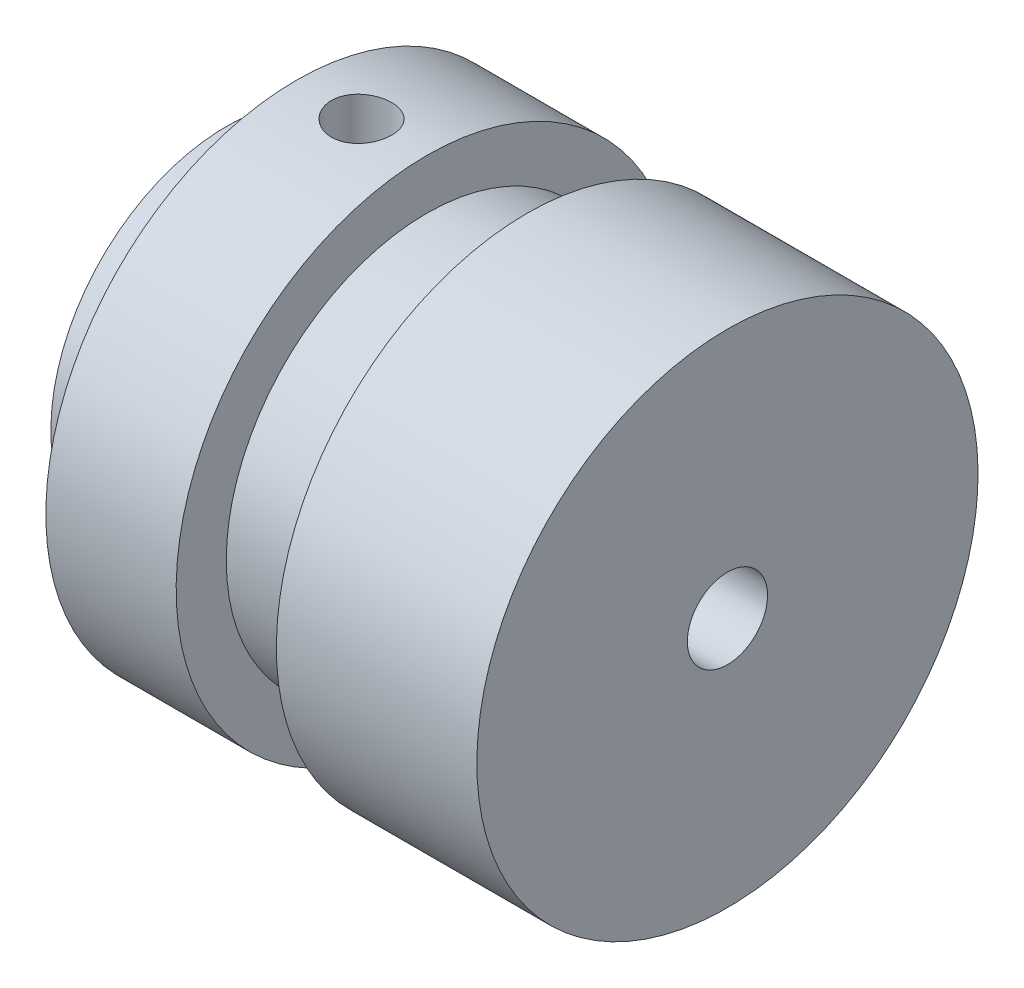
SolidWorks part; units mm, degrees
ref_plane "Front Plane" through (0, 0, 0) normal (0, 0, 1) x (1, 0, 0)
ref_plane "Top Plane" through (0, 0, 0) normal (0, 1, 0) x (1, 0, 0)
ref_plane "Right Plane" through (0, 0, 0) normal (1, 0, 0) x (0, 0, -1)
sketch "Sketch1" plane through (0, 0, 0) normal (0, 0, 1) x (1, 0, 0)
  line L0 (0, 0) -> (0, 20)
  line L2 (5, 25) -> (25, 25)
  line L3 (25, 25) -> (25, 0)
  line L4 (25, 0) -> (0, 0)
  line L5 (0, 4) -> (25, 4)
  line L9 (5, 25) -> (5, 20)
  line L10 (5, 20) -> (0, 20)
  dimension "D1" = 25
  dimension "D2" = 25
  dimension "D3" = 20
  dimension "D4" = 8
  dimension "D8" = 5
revolve "Revolve1" add sketch "Sketch1" angle 360 about L4
mirror "Mirror1" about plane through (0, 0, 0) normal (1, 0, 0) of bodies 101
sketch "Sketch2" plane through (-25, 0, 0) normal (-1, 0, 0) x (0, 0, 1)
  circle A0 centre (0, 0) radius 25
  circle A1 centre (0, 0) radius 17.5
  dimension "D1" = 50
  dimension "D2" = 35
extrude "Cut-Extrude1" cut sketch "Sketch2" against normal blind 7
ref_plane "Plane1" through (0, 25, 0) normal (0, 1, 0) x (1, 0, 0)
sketch "Sketch3" plane through (0, 25, 0) normal (0, 1, 0) x (1, 0, 0)
  line L0 (-5, -25) -> (-5, 25) construction
  line L2 (-5, 25) -> (-18, 25) construction
  circle A0 centre (-11.5, 0) radius 3
  dimension "D1" = 6.5
  dimension "D2" = 6
  dimension "D3" = 25
extrude "Cut-Extrude2" cut sketch "Sketch3" against normal blind 25
